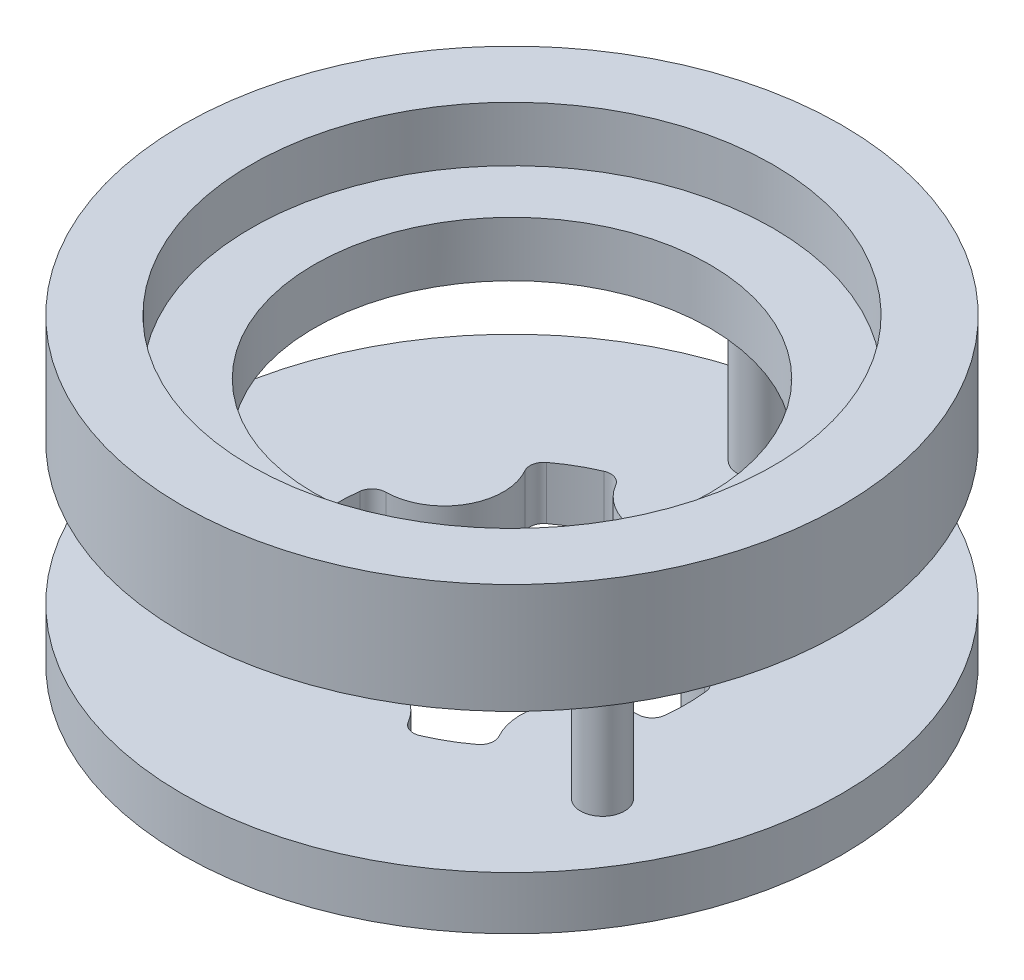
SolidWorks part; units mm, degrees
ref_plane "Front Plane" through (0, 0, 0) normal (0, 0, 1) x (1, 0, 0)
ref_plane "Top Plane" through (0, 0, 0) normal (0, 1, 0) x (1, 0, 0)
ref_plane "Right Plane" through (0, 0, 0) normal (1, 0, 0) x (0, 0, -1)
sketch "Sketch1" plane through (0, 0, 0) normal (0, 1, 0) x (1, 0, 0)
  circle A0 centre (0, 0) radius 31.75 construction
  circle A7 centre (0, 0) radius 6.35
  circle A8 centre (0, 0) radius 60
  arc A9 (-10.16, 30.0805) -> (10.16, 30.0805) centre (0, 33.6183) ccw
  arc A10 (20.9705, 23.8391) -> (31.1305, 6.2414) centre (29.1143, 16.8092) ccw
  arc A11 (31.1305, -6.2414) -> (20.9705, -23.8391) centre (29.1143, -16.8092) ccw
  arc A12 (10.16, -30.0805) -> (-10.16, -30.0805) centre (0, -33.6183) ccw
  arc A13 (-20.9705, -23.8391) -> (-31.1305, -6.2414) centre (-29.1143, -16.8092) ccw
  arc A14 (-31.1305, 6.2414) -> (-20.9705, 23.8391) centre (-29.1143, 16.8092) ccw
  arc A15 (-20.9705, 23.8391) -> (-10.16, 30.0805) centre (0, 0) cw
  arc A16 (10.16, 30.0805) -> (20.9705, 23.8391) centre (0, 0) cw
  arc A17 (31.1305, 6.2414) -> (31.1305, -6.2414) centre (0, 0) cw
  arc A18 (20.9705, -23.8391) -> (10.16, -30.0805) centre (0, 0) cw
  arc A19 (-31.1305, -6.2414) -> (-31.1305, 6.2414) centre (0, 0) cw
  arc A20 (-20.9705, -23.8391) -> (-10.16, -30.0805) centre (0, 0) ccw
  point P7 (0, 31.75)
  point P8 (0, 22.86)
  point P25 (0, 0)
  point P30 (0, 0)
  point P32 (-15.875, 27.4963)
  dimension "D1" = 63.5
  dimension "D4" = 12.7
  dimension "D5" = 120
  dimension "D3" = 8.89
  dimension "D2" = 20.32
  dimension "D6" = 6
extrude "Boss-Extrude1" add sketch "Sketch1" along normal blind 9.652
sketch "Sketch2" plane through (0, 9.652, 0) normal (0, 1, 0) x (1, 0, 0)
  line L0 (0, 0) -> (0, 45) construction
  circle A0 centre (0, 45) radius 4
  circle A1 centre (38.9711, -22.5) radius 4
  circle A2 centre (-38.9711, -22.5) radius 4
  point P11 (0, 0)
  dimension "D1" = 8
  dimension "D2" = 45
  dimension "D3" = 3
extrude "Boss-Extrude2" add sketch "Sketch2" along normal blind 25.4
sketch "Sketch3" plane through (0, 35.052, 0) normal (0, 1, 0) x (1, 0, 0)
  circle A0 centre (0, 0) radius 60 construction
  circle A1 centre (0, 0) radius 60
extrude "Boss-Extrude3" add sketch "Sketch3" along normal blind 20
sketch "Sketch5" plane through (0, 35.052, 0) normal (0, -1, 0) x (1, 0, 0)
  circle A0 centre (0, 0) radius 40
  circle A1 centre (0, 0) radius 36
  dimension "D1" = 80
  dimension "D2" = 72
extrude "Cut-Extrude1" cut sketch "Sketch5" against normal through all contours A1
sketch "Sketch6" plane through (0, 55.052, 0) normal (0, 1, 0) x (1, 0, 0)
  circle A0 centre (0, 0) radius 47.5
  dimension "D1" = 95
extrude "Cut-Extrude2" cut sketch "Sketch6" against normal blind 10
fillet "Fillet1" radius 2.54 12 edges at (-31.1305, 4.826, -6.2414) (-31.1305, 4.826, 6.2414) (-20.9705, 4.826, 23.8391) (-10.16, 4.826, 30.0805) (10.16, 4.826, 30.0805) (20.9705, 4.826, 23.8391) (31.1305, 4.826, 6.2414) (31.1305, 4.826, -6.2414) (20.9705, 4.826, -23.8391) (10.16, 4.826, -30.0805) (-20.9705, 4.826, -23.8391) (-10.16, 4.826, -30.0805)
